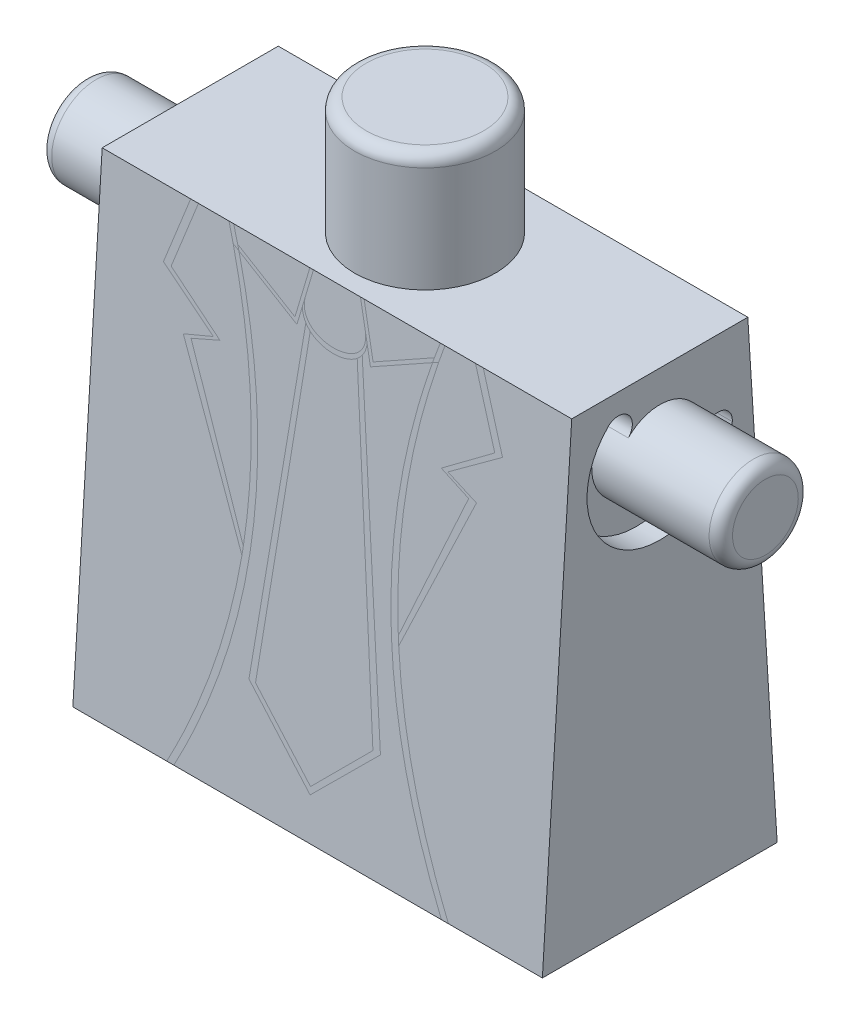
SolidWorks part; units mm, degrees
material "ABS"
ref_plane "Front Plane" through (0, 0, 0) normal (0, 0, 1) x (1, 0, 0)
ref_plane "Top Plane" through (0, 0, 0) normal (0, 1, 0) x (1, 0, 0)
ref_plane "Right Plane" through (0, 0, 0) normal (1, 0, 0) x (0, 0, -1)
sketch "Sketch1" plane through (0, 0, 0) normal (0, 1, 0) x (1, 0, 0)
  line L1 (-10, 0) -> (10, 0)
  line L2 (-10, 0) -> (-10, 10)
  line L3 (-10, 10) -> (10, 10)
  line L4 (10, 0) -> (10, 10)
  point P4 (0, 0)
  dimension "D1" = 20
  dimension "D2" = 10
sketch3d "3DSketch1"
  line L0 (-10, 0, 0) -> (10, 0, -10) construction
  line L1 (10, 0, 0) -> (-10, 0, -10) construction
  line L2 (0, 0, -5) -> (0, 20, -5) construction
  line L4 (10, 20, -1.25) -> (10, 20, -8.75)
  line L5 (10, 20, -1.25) -> (-10, 20, -1.25)
  line L6 (-10, 20, -1.25) -> (-10, 20, -8.75)
  line L7 (10, 20, -8.75) -> (-10, 20, -8.75)
  line L8 (10, 20, -1.25) -> (-10, 20, -8.75) construction
  line L9 (-10, 20, -1.25) -> (10, 20, -8.75) construction
  dimension "D1" = 20
  dimension "D2" = 7.5
  dimension "D3" = 20
loft "Body" add profiles "3DSketch1", "Sketch1"
sketch "Sketch13" plane through (0, 20, 0) normal (0, 1, 0) x (1, 0, 0)
  line L0 (-10, 1.25) -> (10, 8.75) construction
  line L1 (-10, 8.75) -> (10, 1.25) construction
  circle A0 centre (0, 5) radius 3
  dimension "D1" = 6
extrude "Head pin" add sketch "Sketch13" along normal blind 5
sketch "Sketch2" plane through (0, 0, 0) normal (0, -1, 0) x (-1, 0, 0)
  line L0 (-10, 10) -> (10, 10) construction
  line L1 (-8, 8) -> (-2, 8)
  line L2 (-8, 8) -> (-8, 2)
  line L3 (-8, 2) -> (-2, 2)
  line L4 (-2, 8) -> (-2, 2)
  line L5 (-10, 0) -> (-10, 10) construction
  dimension "D1" = 6
  dimension "D2" = 6
  dimension "D3" = 2
  dimension "D4" = 2
extrude "Hip hole part 1" cut sketch "Sketch2" against normal blind 2.5
sketch "Sketch3" plane through (0, 2.5, 0) normal (0, -1, 0) x (1, 0, 0)
  line L1 (8, -8) -> (2, -8)
  line L2 (8, -8) -> (8, -2)
  line L3 (8, -2) -> (2, -2)
  line L4 (2, -8) -> (2, -2)
extrude "Hip hole part 2" cut sketch "Sketch3" against normal blind 2.5 draft 10
hole_wizard "Weight reduction/Make it easy to add centerlines" positions "Sketch17" profile "Sketch18" hole size "Ø3.0" standard "ANSI Metric"
sketch "Sketch17" plane through (0, 5, 0) normal (0, -1, 0) x (-1, 0, 0)
  point P0 (-5, 5)
sketch "Sketch18" plane through (5, 5, -5) normal (1, 0, 0) x (0, 0, -1)
  line L0 (0, 0) -> (0, 2.9013)
  line L1 (0, 2.9013) -> (1.5, 2)
  line L2 (1.5, 2) -> (1.5, 0)
  line L5 (1.5, 0) -> (0, 0)
  line L10 (0, 2.9013) -> (-1.5, 2) construction
  line L11 (0, -6.35) -> (0, 107.95) construction
  dimension "Hole Dia." = 3
  dimension "Hole Depth" = 2
  dimension "Drill Angle" = 118
sketch "Sketch14" plane through (10, 0, 0) normal (1, 0, 0) x (0, 0, -1)
  line L0 (1.25, 20) -> (8.75, 20) construction
  circle A0 centre (5, 16.75) radius 1.9
  point P4 (5, 20)
  dimension "D1" = 3.8
  dimension "D2" = 3.25
extrude "Arm pin" add sketch "Sketch14" along normal blind 4.5
sketch "Sketch15" plane through (10, 0, 0) normal (1, 0, 0) x (0, 0, -1)
  line L0 (3.2322, 18.5178) -> (5, 16.75) construction
  line L1 (5, 16.75) -> (7.4905, 16.5321) construction
  line L2 (5, 16.75) -> (5, 14.25) construction
  line L3 (5, 16.75) -> (5, 14.25) construction
  line L4 (5, 16.75) -> (6.607, 14.8349) construction
  arc A0 (3.2322, 18.5178) -> (7.4905, 16.5321) centre (5, 16.75) ccw construction
  arc A1 (2.808, 18.942) -> (8.0882, 16.4798) centre (5, 16.75) ccw
  arc A2 (3.6565, 18.0935) -> (6.8928, 16.5844) centre (5, 16.75) ccw
  arc A3 (3.6565, 18.0935) -> (2.808, 18.942) centre (3.2322, 18.5178) ccw
  arc A4 (8.0882, 16.4798) -> (6.8928, 16.5844) centre (7.4905, 16.5321) ccw
  point P3 (3.9435, 14.4842)
  dimension "D4" = 0.6
  dimension "D5" = 2.5
  dimension "D1" = 0
  dimension "D2" = 135
  dimension "D3" = 40
  dimension "D6" = 45
extrude "Arm position slot" cut sketch "Sketch15" against normal blind 1
fillet "Easy arm insert" radius 0.5 1 edges at (14.5, 18.65, -5)
mirror "Copying over arm and hip connectors" about plane through (0, 0, 0) normal (1, 0, 0) of "Weight reduction/Make it easy to add centerlines", "Easy arm insert", "Arm pin", "Hip hole part 2", "Hip hole part 1", "Arm position slot"
sketch "Sketch7" plane through (0, 0, 0) normal (0, 0, 1) x (1, 0, 0)
  line L0 (0, 0) -> (0, 20) construction
  line L1 (-10, 20) -> (10, 20) construction
  line L2 (-10, 0) -> (10, 0) construction
  line L3 (-5.9, 20) -> (-6.8919, 17.2749)
  line L4 (-6.8919, 17.2749) -> (-4.7158, 15.6765)
  line L5 (-4.7158, 15.6765) -> (-5.9129, 15.1695)
  line L6 (-5.9129, 15.1695) -> (-3.3, 9)
  line L7 (-4.3766, 19.3) -> (-1.5657, 17.7707)
  line L8 (-1.5657, 17.7707) -> (-1, 20)
  line L9 (3.3, 9) -> (5.9129, 15.1695)
  line L10 (5.9129, 15.1695) -> (4.7158, 15.6765)
  line L11 (4.7158, 15.6765) -> (6.8919, 17.2749)
  line L12 (6.8919, 17.2749) -> (5.9, 20)
  line L13 (1, 20) -> (1.5657, 17.7707)
  line L14 (1.5657, 17.7707) -> (4.3766, 19.3)
  spline S0 degree 2 poles (-6, 0) (-1.1572, 9.639) (-4.6, 20) knots 0 0 0 1 1 1
  spline S1 degree 2 poles (6, 0) (1.1572, 9.639) (4.6, 20) knots 0 0 0 1 1 1
  dimension "D1" = 6
  dimension "D2" = 3.3
  dimension "D3" = 9
  dimension "D4" = 5.4
  dimension "D5" = 6.7
  dimension "D6" = 1.3
  dimension "D7" = 2.7
  dimension "D8" = 2.9
  dimension "D9" = 1.3
  dimension "D10" = 70
  dimension "D11" = 3.2
  dimension "D12" = 0.7
  dimension "D13" = 2.3
  dimension "D14" = 1
  dimension "D15" = 6
  dimension "D16" = 3.3
  dimension "D17" = 9
  dimension "D18" = 5.4
  dimension "D19" = 6.7
  dimension "D20" = 1.3
  dimension "D21" = 2.7
  dimension "D22" = 2.9
  dimension "D23" = 1.3
  dimension "D24" = 70
  dimension "D25" = 3.2
  dimension "D26" = 2.3
  dimension "D27" = 1
  dimension "D28" = 0.7
split line "Shirt and Jacket details"
sketch "Sketch8" plane through (0, 0, 0) normal (0, 0, 1) x (1, 0, 0)
  line L0 (0, 0) -> (0, 20.0305) construction
  line L1 (0, 2) -> (-2.5, 4.5)
  line L2 (-2.5, 4.5) -> (-1, 17.8)
  line L3 (0, 2) -> (2.5, 4.5)
  line L4 (2.5, 4.5) -> (1, 17.8)
  line L5 (-1, 17.8) -> (1, 17.8) construction
  line L6 (-2.5, 4.5) -> (2.5, 4.5) construction
  line L7 (-6, 0) -> (6, 0) construction
  line L8 (-1, 20) -> (-1.5657, 17.7707) construction
  line L9 (1.5657, 17.7707) -> (1, 20) construction
  line L10 (-4.6, 20) -> (-1, 20) construction
  line L11 (1, 20) -> (4.6, 20) construction
  line L12 (-1, 20) -> (1, 20) construction
  line L13 (-1.3806, 18.5) -> (-1.2577, 18.9846) construction
  line L14 (1.3806, 18.5) -> (1.2577, 18.9846) construction
  line L18 (-1, 17.8) -> (-1, 18.01) construction
  line L19 (1, 17.8) -> (1, 18.01) construction
  spline S0 degree 3 poles (-1.3806, 18.5) (-1.2641, 17.1478) (1.2641, 17.1478) (1.3806, 18.5) knots 0 0 0 0 1 1 1 1
  spline S1 degree 3 poles (-1.2577, 18.9846) (-1.7498, 17.2566) (1.7498, 17.2566) (1.2577, 18.9846) knots 0 0 0 0 1 1 1 1
  point P10 (0, 17.8)
  point P11 (0, 4.5)
  dimension "D1" = 2
  dimension "D2" = 5
  dimension "D3" = 2
  dimension "D4" = 4.5
  dimension "D5" = 1.5
  dimension "D6" = 1.5
  dimension "D7" = 2.2
  dimension "D8" = 0.5
  dimension "D9" = 0.5
  dimension "D12" = 0.21
  dimension "D13" = 0.21
split line "Tie details"
sketch "Sketch9" plane through (0, 0, 0) normal (0, 0, 1) x (1, 0, 0)
  line L0 (-1, 17.8) -> (-2.5, 4.5)
  line L1 (-2.5, 4.5) -> (0, 2)
  line L2 (0, 2) -> (2.5, 4.5)
  line L3 (2.5, 4.5) -> (1, 17.8)
  line L4 (-1.2, 18.0073) -> (-2.78, 4.5)
  line L5 (-2.78, 4.5) -> (0, 1.7)
  line L6 (0, 0) -> (0, 20.0305) construction
  line L7 (0, 1.7) -> (2.8201, 4.5)
  line L8 (2.8201, 4.5) -> (1.2, 18.0073)
  line L9 (-1.2, 18.0073) -> (1.2, 18.0073) construction
  spline S0 degree 3 poles (-1.3806, 18.5) (-1.2641, 17.1478) (1.2641, 17.1478) (1.3806, 18.5) knots 0 0 0 0 1 1 1 1 construction
  dimension "D1" = 0.3
  dimension "D2" = 0.28
  dimension "D3" = 2.4
split line "Tie borderline"
sketch "Sketch10" plane through (0, 0, 0) normal (0, 0, 1) x (1, 0, 0)
  line L0 (-5.9, 20) -> (-6.23, 20) construction
  line L1 (-10, 20) -> (-5.9, 20) construction
  line L2 (-6.8919, 17.2749) -> (-7.2219, 17.2749) construction
  line L3 (-4.7158, 15.6765) -> (-4.9958, 15.6765) construction
  line L4 (-5.9129, 15.1695) -> (-6.2429, 15.1695) construction
  line L5 (-6.23, 20) -> (-7.2219, 17.2749)
  line L6 (-7.2219, 17.2749) -> (-4.9958, 15.6765)
  line L7 (-4.9958, 15.6765) -> (-6.2429, 15.1695)
  line L8 (-6.2429, 15.1695) -> (-3.3391, 8.65)
  line L9 (5.9, 20) -> (6.23, 20) construction
  line L10 (5.9, 20) -> (10, 20) construction
  line L11 (6.8919, 17.2749) -> (7.2219, 17.2749) construction
  line L12 (4.7158, 15.6765) -> (4.9958, 15.6765) construction
  line L13 (5.9129, 15.1695) -> (6.2429, 15.1695) construction
  line L14 (6.23, 20) -> (7.2219, 17.2749)
  line L15 (7.2219, 17.2749) -> (4.9958, 15.6765)
  line L16 (4.9958, 15.6765) -> (6.2429, 15.1695)
  line L17 (6.2429, 15.1695) -> (3.3391, 8.65)
  spline S0 degree 3 poles (-3.3, 9) (-3.3811, 8.2221) (-3.5003, 7.4458) (-3.8156, 5.8964) (-4.0108, 5.1294) (-4.6966, 2.8717) (-5.2892, 1.4148) (-6, 0) knots 0 0 0 0 0.25 0.25 0.5 0.5 1 1 1 1 construction
  spline S1 degree 3 poles (3.3, 9) (3.3811, 8.2221) (3.5003, 7.4458) (3.8156, 5.8964) (4.0108, 5.1294) (4.6966, 2.8717) (5.2892, 1.4148) (6, 0) knots 0 0 0 0 0.25 0.25 0.5 0.5 1 1 1 1 construction
  dimension "D1" = 0.35
  dimension "D2" = 0.33
  dimension "D3" = 0.28
  dimension "D4" = 0.33
  dimension "D5" = 0.33
  dimension "D6" = 0.33
  dimension "D7" = 0.33
  dimension "D8" = 0.28
  dimension "D9" = 0.33
  dimension "D10" = 0.35
split line "Jacket borderline"
sketch "Sketch11" plane through (0, 0, 0) normal (0, 0, 1) x (1, 0, 0)
  line L0 (-6, 0) -> (6, 0) construction
  line L1 (-4.6, 20) -> (-1, 20) construction
  line L2 (-4.6, 20) -> (-4.4, 20) construction
  line L3 (-3.3, 9) -> (-3, 9) construction
  line L4 (-6, 0) -> (-5.7, 0) construction
  line L5 (5.7, 0) -> (6, 0) construction
  line L6 (3, 9) -> (3.3, 9) construction
  line L7 (4.4, 20) -> (4.6, 20) construction
  line L8 (1, 20) -> (4.6, 20) construction
  spline S0 degree 2 poles (-5.7, 0) (-0.8137, 9.65) (-4.4, 20) knots 0 0 0 1 1 1
  spline S1 degree 2 poles (4.4, 20) (0.8137, 9.65) (5.7, 0) knots 0 0 0 1 1 1
  dimension "D1" = 0.2
  dimension "D2" = 0.3
  dimension "D3" = 0.3
  dimension "D4" = 0.2
  dimension "D5" = 0.3
  dimension "D6" = 0.3
split line "Shirt and Jacket borderline"
sketch "Sketch12" plane through (0, 0, 0) normal (0, 0, 1) x (1, 0, 0)
  line L0 (1.2774, 18.9067) -> (1.2577, 18.9846) construction
  line L2 (-1, 20) -> (-1.1548, 20) construction
  line L3 (-4.4, 20) -> (-1, 20) construction
  line L4 (1, 20) -> (1.1548, 20) construction
  line L5 (1, 20) -> (4.4, 20) construction
  line L6 (-1.1548, 20) -> (-1.6636, 17.9947)
  line L7 (-1.6636, 17.9947) -> (-4.1889, 19.3686)
  line L8 (1.1548, 20) -> (1.6636, 17.9947)
  line L9 (1.6636, 17.9947) -> (4.1889, 19.3686)
  line L10 (-1.5657, 17.7707) -> (-4.1232, 19.1621) construction
  line L11 (4.1232, 19.1621) -> (1.5657, 17.7707) construction
  line L12 (-1, 20) -> (-1.2577, 18.9846) construction
  spline S0 degree 3 poles (-4.4, 20) (-4.3037, 19.7219) (-4.2113, 19.4427) (-4.1232, 19.1621) knots 0 0 0 0 1 1 1 1 construction
  spline S1 degree 3 poles (4.1232, 19.1621) (4.2113, 19.4427) (4.3037, 19.7219) (4.4, 20) knots 0 0 0 0 1 1 1 1 construction
  dimension "D1" = 0.15
  dimension "D2" = 0.15
  dimension "D3" = 0.15
  dimension "D4" = 0.15
split line "Shirt borderline"
fillet "Easy head insert" radius 0.5 1 edges at (0, 25, -2)
fillet "Smoothing edges" [suppressed] radius 0.1
scale "Scale1" scale about centroid uniform scaling yes scale factor 2
